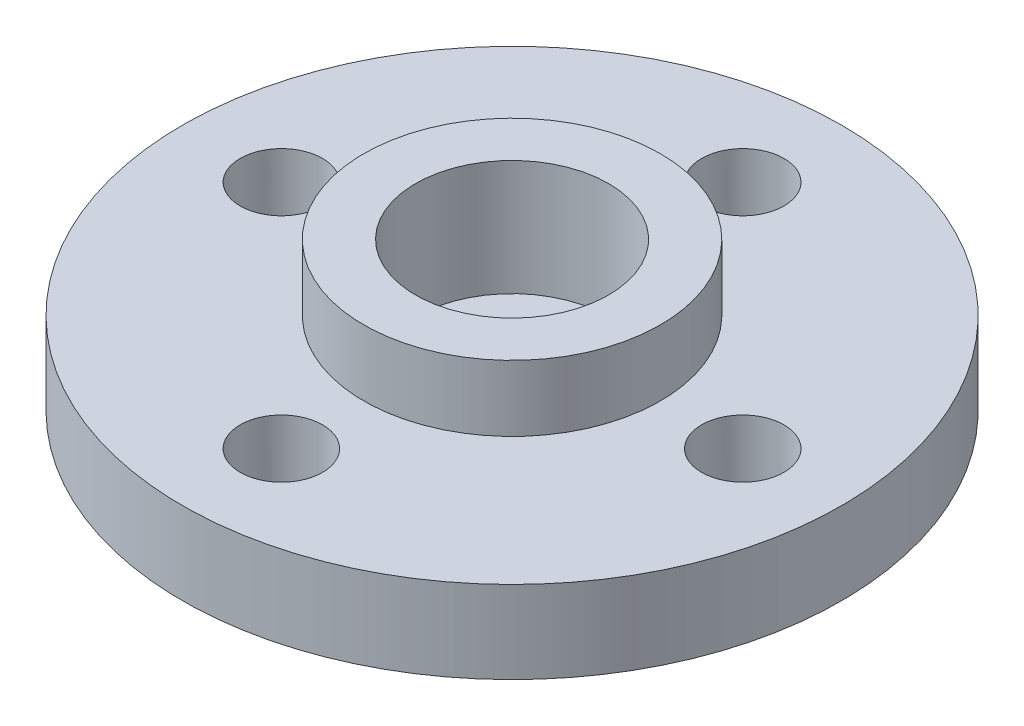
SolidWorks part; units mm, degrees
ref_plane "Front Plane" through (0, 0, 0) normal (0, 0, 1) x (1, 0, 0)
ref_plane "Top Plane" through (0, 0, 0) normal (0, 1, 0) x (1, 0, 0)
ref_plane "Right Plane" through (0, 0, 0) normal (1, 0, 0) x (0, 0, -1)
sketch "Sketch1" plane through (0, 0, 0) normal (1, 0, 0) x (0, 0, -1)
  line L0 (1.6, 0) -> (1.6, 1)
  line L1 (1.6, 1) -> (2.93, 1)
  line L2 (2.93, 1) -> (2.93, 4.5)
  line L3 (2.93, 4.5) -> (4.5, 4.5)
  line L4 (4.5, 4.5) -> (4.5, 2.5)
  line L5 (4.5, 2.5) -> (10, 2.5)
  line L6 (10, 2.5) -> (10, 0)
  line L7 (10, 0) -> (1.6, 0)
  line L8 (0, 0) -> (0, 4.5) construction
  dimension "D1" = 3.2
  dimension "D2" = 5.86
  dimension "D3" = 20
  dimension "D4" = 2.5
  dimension "D5" = 4.5
  dimension "D6" = 9
  dimension "D7" = 3.5
revolve "Revolve1" add sketch "Sketch1" angle 360 about L8
hole_wizard "M3 Tapped Hole1" positions "Sketch2" profile "Sketch3" tap size "M3" standard "ISO" end condition through all
sketch "Sketch2" plane through (0, 0, 0) normal (0, -1, 0) x (-1, 0, 0)
  point P0 (0, -7)
  dimension "D1" = 7
sketch "Sketch3" plane through (0, 0, 7) normal (1, 0, 0) x (0, 0, -1)
  line L0 (0, 0) -> (0, 4.5)
  line L1 (0, 4.5) -> (1.25, 4.5)
  line L2 (1.25, 4.5) -> (1.25, 0)
  line L5 (1.25, 0) -> (0, 0)
  line L11 (0, -6.35) -> (0, 107.95) construction
  dimension "Thru Tap Drill Dia." = 2.5
  dimension "Thru Tap Drill Depth" = 4.5
cosmetic thread "Hole Thread1" parameters "D2"=3
pattern_circular "CirPattern1" count 4 over 360 about axis through (0, 0, 0) along (0, 1, 0) of "M3 Tapped Hole1"
cosmetic thread "Hole Thread2" parameters "D2"=3
cosmetic thread "Hole Thread3" parameters "D2"=3
cosmetic thread "Hole Thread4" parameters "D2"=3
move or copy body "Body-Move/Copy1" [suppressed]
